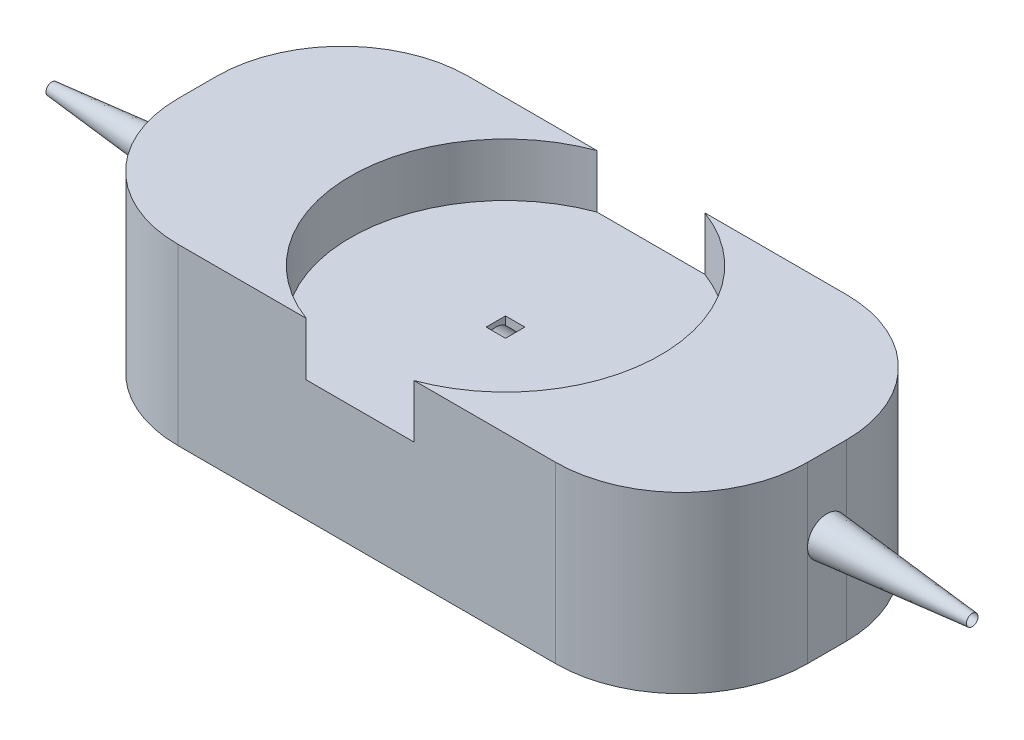
SolidWorks part; units mm, degrees
ref_plane "Front Plane" through (0, 0, 0) normal (0, 0, 1) x (1, 0, 0)
ref_plane "Top Plane" through (0, 0, 0) normal (0, 1, 0) x (1, 0, 0)
ref_plane "Right Plane" through (0, 0, 0) normal (1, 0, 0) x (0, 0, -1)
sketch "Sketch1" plane through (0, 0, 0) normal (0, 1, 0) x (1, 0, 0)
  line L1 (-25, -15) -> (40, -15)
  line L2 (-25, -15) -> (-25, 15)
  line L3 (-25, 15) -> (40, 15)
  line L4 (40, -15) -> (40, 15)
  line L5 (-25, -15) -> (40, 15) construction
  line L6 (-25, 15) -> (40, -15) construction
  point P0 (0, 0)
  dimension "D1" = 30
  dimension "D2" = 65
extrude "Boss-Extrude1" add sketch "Sketch1" along normal blind 58
sketch "Sketch3" plane through (-25, 0, 0) normal (-1, 0, 0) x (0, 0, 1)
  line L0 (-15, 58) -> (15, 58) construction
  circle A0 centre (0, 50.4) radius 1.6
  dimension "D1" = 3.2
  dimension "D2" = 7.6
fillet "Fillet1" radius 13 4 edges at (40, 29, -15) (-25, 29, -15) (40, 29, 15) (-25, 29, 15)
ref_plane "Plane2" through (0, -10, 0) normal (0, -1, 0) x (-1, 0, 0)
sketch "Sketch15" plane through (0, -10, 0) normal (0, -1, 0) x (-1, 0, 0)
  line L1 (-41.9055, 15.8797) -> (41.7906, 15.8797)
  line L2 (-41.9055, 15.8797) -> (-41.9055, -15.8187)
  line L3 (-41.9055, -15.8187) -> (41.7906, -15.8187)
  line L4 (41.7906, 15.8797) -> (41.7906, -15.8187)
extrude "Cut-Extrude7" cut sketch "Sketch15" against normal blind 50
ref_plane "Plane3" through (0, 40, 0) normal (0, -1, 0) x (-1, 0, 0)
ref_plane "Plane4" through (0, 58, 0) normal (0, 1, 0) x (1, 0, 0)
sketch "Sketch18" plane through (0, 58, 0) normal (0, 1, 0) x (1, 0, 0)
  circle A0 centre (6.8285, 0) radius 16
  dimension "D1" = 32
extrude "Cut-Extrude10" cut sketch "Sketch18" against normal blind 5.5
extrude "Cut-Extrude12" cut sketch "Sketch3" against normal up to next
ref_plane "Plane5" through (0, 52.5, 0) normal (0, 1, 0) x (1, 0, 0)
sketch "Sketch21" plane through (0, 52.5, 0) normal (0, 1, 0) x (1, 0, 0)
  line L1 (5.8285, -1) -> (7.8285, -1)
  line L2 (5.8285, -1) -> (5.8285, 1)
  line L3 (5.8285, 1) -> (7.8285, 1)
  line L4 (7.8285, -1) -> (7.8285, 1)
  line L5 (5.8285, -1) -> (7.8285, 1) construction
  line L6 (5.8285, 1) -> (7.8285, -1) construction
  point P0 (6.8285, 0)
  dimension "D1" = 2
  dimension "D2" = 2
extrude "Cut-Extrude13" cut sketch "Sketch21" against normal blind 8
ref_plane "Plane7" through (-25, 0, 0) normal (-1, 0, 0) x (0, 0, 1)
sketch "Sketch24" plane through (0, 0, 0) normal (0, 0, 1) x (1, 0, 0)
  line L0 (-25, 51) -> (-25, 52.4)
  line L1 (-25, 52) -> (-25, 48.8) construction
  line L2 (-25, 27.72) -> (-25, -27.72) construction
  line L3 (-25, 52.4) -> (-40, 51)
  line L4 (-40, 51) -> (-25, 51)
  line L5 (-25, 50.4) -> (-31.2466, 50.4) construction
  line L6 (-25, 40) -> (-25, 58) construction
  line L7 (-25, 50.4) -> (46.09, 50.4) construction
  dimension "D1" = 0.6
  dimension "D2" = 2
  dimension "D3" = 15
revolve "Revolve1" add sketch "Sketch24" angle 360 about L5
sketch "Sketch25" plane through (0, 0, 0) normal (0, 0, 1) x (1, 0, 0)
  line L4 (39.9952, 52.4) -> (54.9952, 51)
  line L5 (54.9952, 51) -> (39.9952, 51)
  line L6 (39.9952, 51) -> (39.9952, 52.4)
  line L7 (-25, 50.4) -> (46.09, 50.4) construction
  dimension "D1" = 0.6
  dimension "D2" = 2
  dimension "D3" = 15
revolve "Revolve2" add sketch "Sketch25" angle 360 about L7
